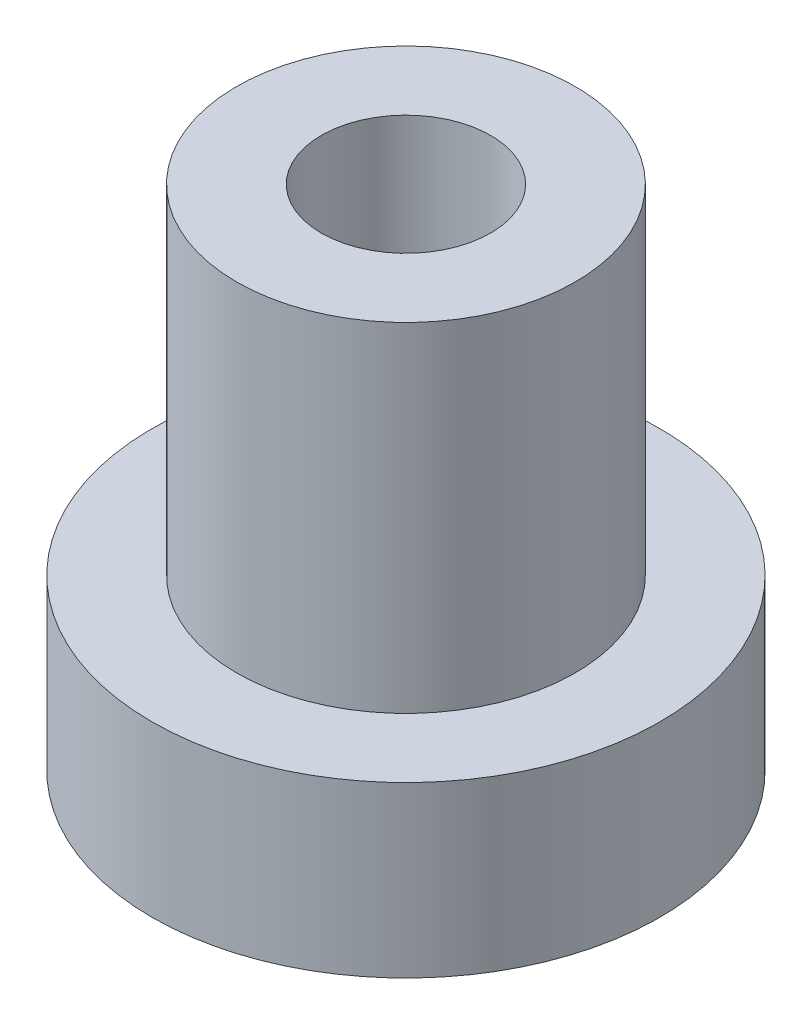
SolidWorks part; units mm, degrees
material "Custom Plastic"
ref_plane "Front Plane" through (0, 0, 0) normal (0, 0, 1) x (1, 0, 0)
ref_plane "Top Plane" through (0, 0, 0) normal (0, 1, 0) x (1, 0, 0)
ref_plane "Right Plane" through (0, 0, 0) normal (1, 0, 0) x (0, 0, -1)
other "Configuration Table"
sketch "Sketch1" plane through (0, 0, 0) normal (0, 0, 1) x (1, 0, 0)
  line L0 (0, 0) -> (0, -15.812) construction
  line L1 (0, 0) -> (-9.525, 0)
  line L2 (-9.525, 0) -> (-9.525, 6.35)
  line L3 (-9.525, 6.35) -> (-6.35, 6.35)
  line L4 (-6.35, 6.35) -> (-6.35, 19.05)
  line L5 (-6.35, 19.05) -> (-3.175, 19.05)
  line L6 (-3.175, 19.05) -> (-3.175, 6.35)
  line L7 (-3.175, 6.35) -> (0, 6.35)
  line L8 (0, 6.35) -> (0, 0)
  dimension "D1" = 6.35
  dimension "D2" = 19.05
  dimension "D3" = 12.7
  dimension "D4" = 12.7
  dimension "D6" = 6.35
revolve "Revolve1" add sketch "Sketch1" angle 360 about L0
